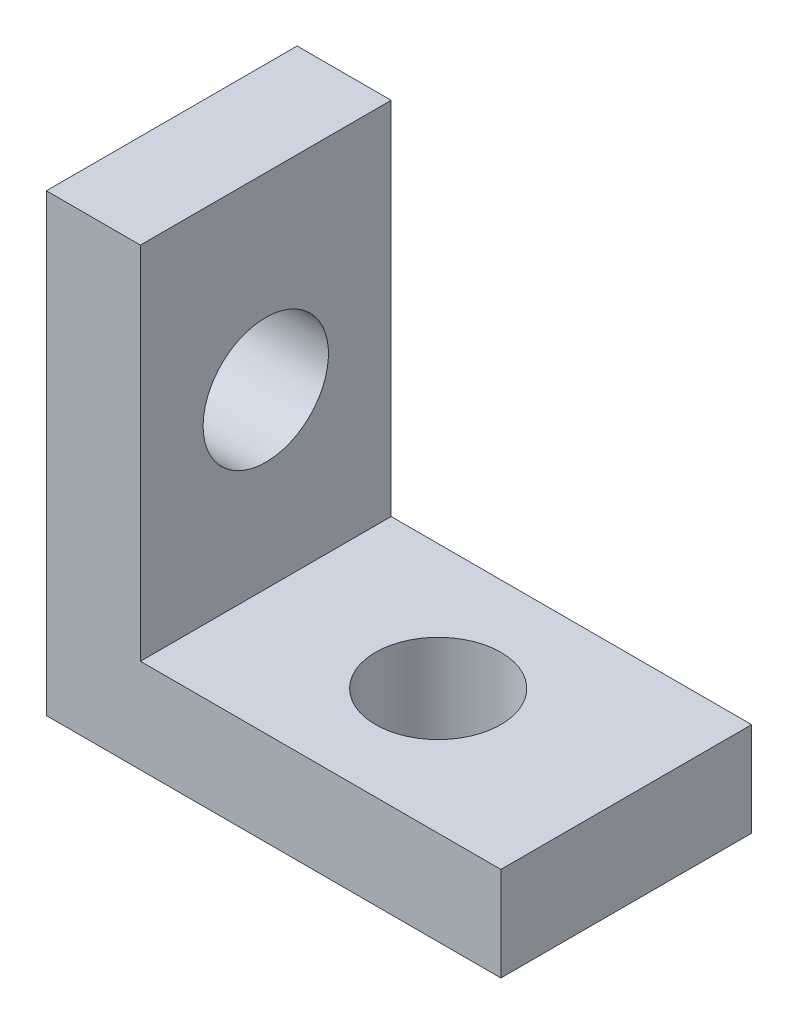
SolidWorks part; units mm, degrees
ref_plane "前视基准面" through (0, 0, 0) normal (0, 0, 1) x (1, 0, 0)
ref_plane "上视基准面" through (0, 0, 0) normal (0, 1, 0) x (1, 0, 0)
ref_plane "右视基准面" through (0, 0, 0) normal (1, 0, 0) x (0, 0, -1)
sketch "草图1" plane through (0, 0, 0) normal (0, 0, 1) x (1, 0, 0)
  line L0 (0, 0) -> (14.5, 0)
  line L1 (0, 0) -> (0, 14.5)
  line L2 (0, 14.5) -> (3, 14.5)
  line L3 (14.5, 0) -> (14.5, 3)
  line L4 (14.5, 3) -> (3, 3)
  line L5 (3, 3) -> (3, 14.5)
extrude "凸台-拉伸1" add sketch "草图1" along normal blind 8
sketch "草图2" plane through (0, 0, 0) normal (0, -1, 0) x (1, 0, 0)
  circle A0 centre (8.5, 4) radius 2
extrude "切除-拉伸1" cut sketch "草图2" against normal through all
sketch "草图3" plane through (0, 0, 0) normal (-1, 0, 0) x (0, 0, 1)
  circle A0 centre (4, 8.5) radius 2
  point P2 (-12.6491, 2.4596)
  point P3 (0, 0)
extrude "切除-拉伸3" cut sketch "草图3" against normal blind 8 contours A0
